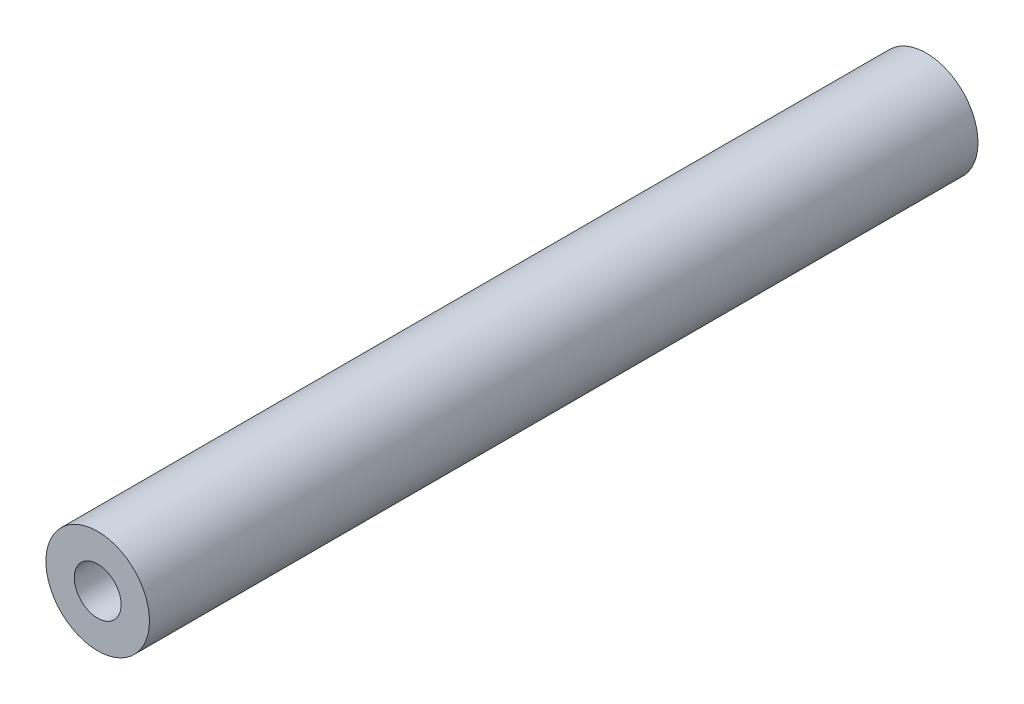
SolidWorks part; units mm, degrees
ref_plane "Front Plane" through (0, 0, 0) normal (0, 0, 1) x (1, 0, 0)
ref_plane "Top Plane" through (0, 0, 0) normal (0, 1, 0) x (1, 0, 0)
ref_plane "Right Plane" through (0, 0, 0) normal (1, 0, 0) x (0, 0, -1)
sketch "Croquis1" plane through (0, 0, 0) normal (0, 0, 1) x (1, 0, 0)
  circle A0 centre (0, 0) radius 12.7
  dimension "D1" = 25.4
extrude "Saliente-Extruir2" add sketch "Croquis1" along normal mid plane 203.2
hole_wizard "Taladro roscado 1/2-201" positions "Croquis3" profile "Croquis2" tap size "1/2-20" standard "Ansi Inch"
sketch "Croquis3" plane through (0, 0, 101.6) normal (0, 0, 1) x (1, 0, 0)
  point P0 (0, 0)
sketch "Croquis2" plane through (0, 0, 101.6) normal (1, 0, 0) x (0, -1, 0)
  line L0 (0, 0) -> (0, 35.2076)
  line L1 (0, 35.2076) -> (5.7544, 31.75)
  line L2 (5.7544, 31.75) -> (5.7544, 0)
  line L5 (5.7544, 0) -> (0, 0)
  line L10 (0, 35.2076) -> (-5.7544, 31.75) construction
  line L11 (0, -6.35) -> (0, 107.95) construction
  dimension "Diámetro de perforador para roscar" = 11.5087
  dimension "Profundidad de perforador para roscar" = 31.75
  dimension "Ángulo de perforador" = 118
cosmetic thread "Rosca de taladro1" parameters "D1"=25.4, "D2"=12.7
hole_wizard "Taladro roscado 5/16-181" positions "Croquis5" profile "Croquis4" tap size "5/16-18" standard "Ansi Inch"
sketch "Croquis5" plane through (0, 0, -101.6) normal (0, 0, -1) x (-1, 0, 0)
  point P0 (0, 0)
sketch "Croquis4" plane through (0, 0, -101.6) normal (1, 0, 0) x (0, 1, 0)
  line L0 (0, 0) -> (0, 21.7096)
  line L1 (0, 21.7096) -> (3.2639, 19.7485)
  line L2 (3.2639, 19.7485) -> (3.2639, 0)
  line L5 (3.2639, 0) -> (0, 0)
  line L10 (0, 21.7096) -> (-3.2639, 19.7485) construction
  line L11 (0, -6.35) -> (0, 107.95) construction
  dimension "Diámetro de perforador para roscar" = 6.5278
  dimension "Profundidad de perforador para roscar" = 19.7485
  dimension "Ángulo de perforador" = 118
cosmetic thread "Rosca de taladro2" parameters "D1"=12.7, "D2"=7.9375
